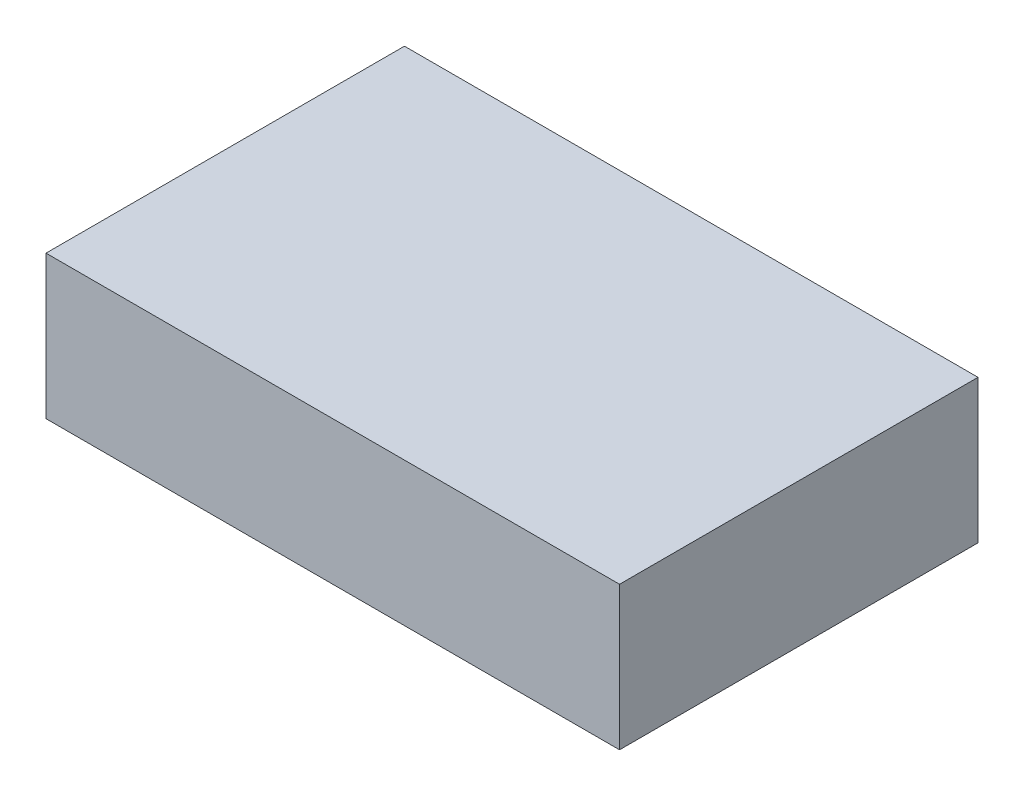
SolidWorks part; units mm, degrees
ref_plane "Front Plane" through (0, 0, 0) normal (0, 0, 1) x (1, 0, 0)
ref_plane "Top Plane" through (0, 0, 0) normal (0, 1, 0) x (1, 0, 0)
ref_plane "Right Plane" through (0, 0, 0) normal (1, 0, 0) x (0, 0, -1)
sketch "Sketch1" plane through (0, 0, 0) normal (0, 1, 0) x (1, 0, 0)
  line L1 (-20, -12.5) -> (20, -12.5)
  line L2 (-20, -12.5) -> (-20, 12.5)
  line L3 (-20, 12.5) -> (20, 12.5)
  line L4 (20, -12.5) -> (20, 12.5)
  line L5 (-20, -12.5) -> (20, 12.5) construction
  line L6 (-20, 12.5) -> (20, -12.5) construction
  point P0 (0, 0)
  dimension "D1" = 25
  dimension "D2" = 40
extrude "Boss-Extrude1" add sketch "Sketch1" along normal blind 10 contours L2 L3 L4 L1
